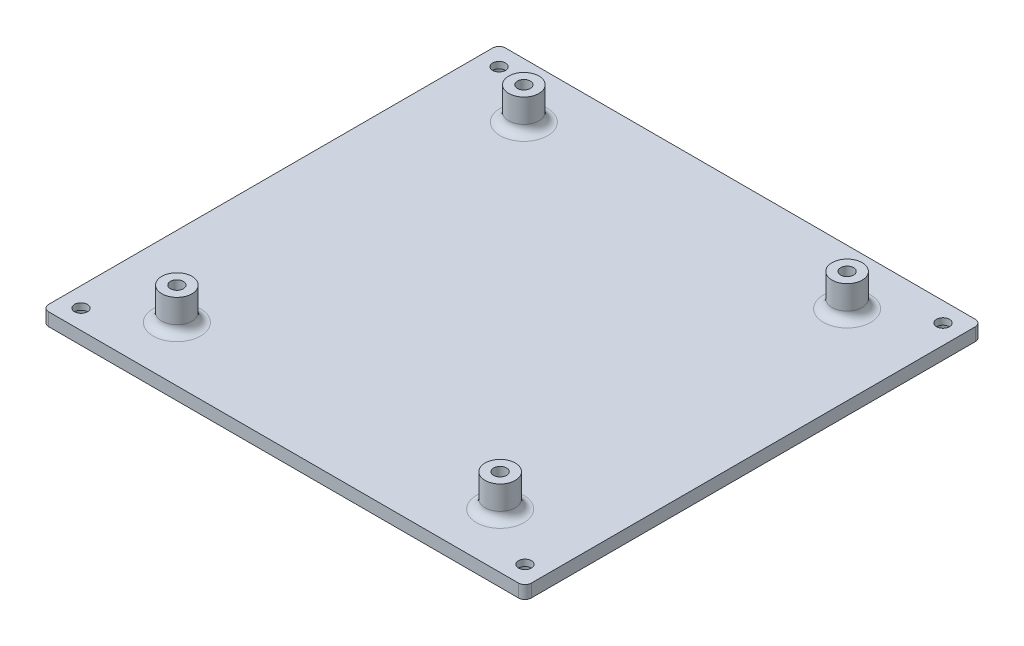
SolidWorks part; units mm, degrees
ref_plane "Front Plane" through (0, 0, 0) normal (0, 0, 1) x (1, 0, 0)
ref_plane "Top Plane" through (0, 0, 0) normal (0, 1, 0) x (1, 0, 0)
ref_plane "Right Plane" through (0, 0, 0) normal (1, 0, 0) x (0, 0, -1)
sketch "Sketch2" plane through (0, 0, 0) normal (0, 1, 0) x (1, 0, 0)
  line L1 (-56, -53) -> (56, -53)
  line L2 (-56, -53) -> (-56, 53)
  line L3 (-56, 53) -> (56, 53)
  line L4 (56, -53) -> (56, 53)
  line L5 (-56, -53) -> (56, 53) construction
  line L6 (-56, 53) -> (56, -53) construction
  point P0 (0, 0)
  dimension "D1" = 112
  dimension "D2" = 106
extrude "Boss-Extrude1" add sketch "Sketch2" along normal blind 3
sketch "Sketch3" plane through (0, 3, 0) normal (0, 1, 0) x (1, 0, 0)
  line L1 (-37.5, -40.25) -> (37.5, -40.25)
  line L2 (-37.5, -40.25) -> (-37.5, 40.25)
  line L3 (-37.5, 40.25) -> (37.5, 40.25)
  line L4 (37.5, -40.25) -> (37.5, 40.25)
  line L5 (-37.5, -40.25) -> (37.5, 40.25) construction
  line L6 (-37.5, 40.25) -> (37.5, -40.25) construction
  circle A0 centre (37.5, 40.25) radius 3.5
  circle A1 centre (-37.5, 40.25) radius 3.5
  circle A2 centre (-37.5, -40.25) radius 3.5
  circle A3 centre (37.5, -40.25) radius 3.5
  point P0 (0, 0)
  dimension "D1" = 75
  dimension "D2" = 80.5
extrude "Boss-Extrude2" add sketch "Sketch3" along normal blind 7.5 contours L3 A1 L2 | L2 A1 L3 | L4 A0 L3 | L3 A0 L4 | L2 A2 L1 | L1 A2 L2 | L1 A3 L4 | L4 A3 L1
sketch "Sketch4" plane through (0, 10.5, 0) normal (0, 1, 0) x (1, 0, 0)
  circle A0 centre (-37.5, 40.25) radius 1.5
  circle A1 centre (37.5, 40.25) radius 1.5
  circle A2 centre (37.5, -40.25) radius 1.5
  circle A3 centre (-37.5, -40.25) radius 1.5
extrude "Cut-Extrude1" cut sketch "Sketch4" against normal blind 5
sketch "Sketch6" plane through (0, 3, 0) normal (0, 1, 0) x (1, 0, 0)
  line L1 (-51.5, -48.5) -> (51.5, -48.5)
  line L2 (-51.5, -48.5) -> (-51.5, 48.5)
  line L3 (-51.5, 48.5) -> (51.5, 48.5)
  line L4 (51.5, -48.5) -> (51.5, 48.5)
  line L5 (-51.5, -48.5) -> (51.5, 48.5) construction
  line L6 (-51.5, 48.5) -> (51.5, -48.5) construction
  circle A0 centre (-51.5, 48.5) radius 1.5
  circle A1 centre (-51.5, -48.5) radius 1.5
  circle A2 centre (51.5, -48.5) radius 1.5
  circle A3 centre (51.5, 48.5) radius 1.5
  point P0 (0, 0)
  dimension "D1" = 103
  dimension "D2" = 97
extrude "Cut-Extrude4" cut sketch "Sketch6" against normal blind 3 contours L3 A0 L2 | L2 A0 L3 | L2 A1 L1 | L1 A1 L2 | L1 A2 L4 | L4 A2 L1 | L4 A3 L3 | L3 A3 L4
sketch "Sketch7" plane through (0, 0, 0) normal (0, -1, 0) x (1, 0, 0)
  line L1 (-51.5, -48.5) -> (51.5, -48.5)
  line L2 (-51.5, -48.5) -> (-51.5, 48.5)
  line L3 (-51.5, 48.5) -> (51.5, 48.5)
  line L4 (51.5, -48.5) -> (51.5, 48.5)
  line L5 (-51.5, -48.5) -> (51.5, 48.5) construction
  line L6 (-51.5, 48.5) -> (51.5, -48.5) construction
  circle A0 centre (-51.5, 48.5) radius 2.5
  circle A1 centre (-51.5, -48.5) radius 2.5
  circle A2 centre (51.5, -48.5) radius 2.5
  circle A3 centre (51.5, 48.5) radius 2.5
  point P0 (0, 0)
  point P11 (-109.1277, 32.8193)
  circle M1 centre (51.5, -48.5) radius 1.5
  circle M2 centre (51.5, 48.5) radius 1.5
  circle M3 centre (-51.5, 48.5) radius 1.5
  circle M4 centre (-51.5, -48.5) radius 1.5
extrude "Cut-Extrude5" cut sketch "Sketch7" against normal blind 1.5 contours L3 A0 L2 M3 | L2 L3 M3 | L3 L2 M3 | L2 A0 L3 M3 | L1 L2 M4 | L2 A1 L1 M4 | L2 L1 M4 | L1 A1 L2 M4 | L1 A2 L4 M1 | L4 L1 M1 | L1 L4 M1 | L4 A2 L1 M1 | L4 L3 M2 | L4 A3 L3 M2 | L4 L3 M2 | L3 A3 L4 M2
fillet "Fillet1" radius 1.5 4 edges at (-56, 1.5, -53) (56, 1.5, -53) (56, 1.5, 53) (-56, 1.5, 53)
fillet "Fillet2" radius 2 4 edges at (37.5, 3, -43.75) (37.5, 3, 36.75) (-37.5, 3, -43.75) (-37.5, 3, 36.75)
